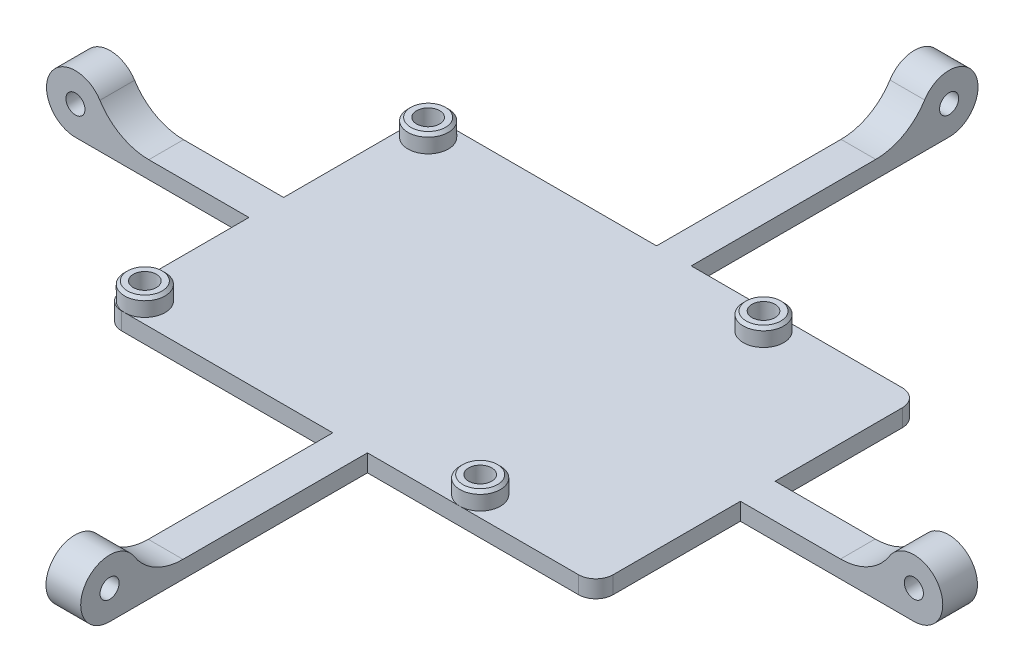
SolidWorks part; units mm, degrees
ref_plane "Front Plane" through (0, 0, 0) normal (0, 0, 1) x (1, 0, 0)
ref_plane "Top Plane" through (0, 0, 0) normal (0, 1, 0) x (1, 0, 0)
ref_plane "Right Plane" through (0, 0, 0) normal (1, 0, 0) x (0, 0, -1)
sketch "Sketch1" plane through (0, 0, 0) normal (0, 1, 0) x (1, 0, 0)
  line L0 (-39, 24.5) -> (-39, -24.5) construction
  line L1 (-39.5, -28) -> (39.5, -28)
  line L2 (-42.5, -25) -> (-42.5, 25)
  line L3 (-39.5, 28) -> (39.5, 28)
  line L4 (42.5, -25) -> (42.5, 25)
  line L5 (-42.5, -28) -> (42.5, 28) construction
  line L6 (-42.5, 28) -> (42.5, -28) construction
  line L7 (-39, 24.5) -> (19, 24.5) construction
  line L8 (-39, -24.5) -> (19, -24.5) construction
  circle A0 centre (-39, -24.5) radius 2
  circle A1 centre (-39, 24.5) radius 2
  circle A2 centre (19, 24.5) radius 2
  circle A3 centre (19, -24.5) radius 2
  arc A4 (39.5, 28) -> (42.5, 25) centre (39.5, 25) cw
  arc A5 (39.5, -28) -> (42.5, -25) centre (39.5, -25) ccw
  arc A6 (-39.5, -28) -> (-42.5, -25) centre (-39.5, -25) cw
  arc A7 (-42.5, 25) -> (-39.5, 28) centre (-39.5, 25) cw
  point P0 (0, 0)
  dimension "D3" = 4
  dimension "D8" = 3
  dimension "D1" = 56
  dimension "D2" = 85
  dimension "D4" = 3.5
  dimension "D5" = 3.5
  dimension "D6" = 3.5
  dimension "D7" = 58
extrude "Boss-Extrude1" add sketch "Sketch1" along normal blind 3
sketch "Sketch3" plane through (0, 3, 0) normal (0, 1, 0) x (1, 0, 0)
  line L0 (-72.5, 0) -> (72.5, 0) construction
  line L1 (42.5, -25) -> (42.5, 25) construction
  line L2 (0, 72.5) -> (0, -72.5) construction
  line L3 (-3, 3) -> (-72.5, 3)
  line L5 (-3, -3) -> (-72.5, -3)
  line L6 (-72.5, 3) -> (-72.5, -3)
  line L7 (-3, 3) -> (-3, 72.5)
  line L9 (42.5, 3) -> (42.5, -3)
  line L12 (3, 3) -> (3, 72.5)
  line L13 (3, 72.5) -> (-3, 72.5)
  line L14 (3, 3) -> (72.5, 3)
  line L15 (3, -3) -> (72.5, -3)
  line L16 (72.5, -3) -> (72.5, 3)
  line L17 (3, -3) -> (3, -72.5)
  line L18 (-3, -3) -> (-3, -72.5)
  line L19 (-3, -72.5) -> (3, -72.5)
  point P4 (0, 0)
  point P18 (0, 0)
  point P28 (0, 0)
  dimension "D1" = 30
  dimension "D2" = 6
  dimension "D3" = 4
extrude "Boss-Extrude3" add sketch "Sketch3" against normal blind 3 contours L5 L6 L3 L7 L13 L12 L14 L16 L15 L17 L19 L18
ref_axis "Axis1" through (0, 0, 0) along (0, 1, 0)
sketch "Sketch2" plane through (0, 3, 0) normal (0, 1, 0) x (1, 0, 0)
  circle A0 centre (19, 24.5) radius 2 construction
  circle A1 centre (19, -24.5) radius 2 construction
  circle A2 centre (-39, -24.5) radius 2 construction
  circle A3 centre (-39, 24.5) radius 2 construction
  circle A4 centre (19, 24.5) radius 2
  circle A5 centre (19, -24.5) radius 2
  circle A6 centre (-39, -24.5) radius 2
  circle A7 centre (-39, 24.5) radius 2
  circle A8 centre (-39, -24.5) radius 3.5
  circle A9 centre (-39, 24.5) radius 3.5
  circle A10 centre (19, 24.5) radius 3.5
  circle A11 centre (19, -24.5) radius 3.5
  dimension "D1" = 7
extrude "Boss-Extrude2" add sketch "Sketch2" along normal blind 3
sketch "Sketch4" plane through (0, 0, 3) normal (0, 0, 1) x (1, 0, 0)
  line L0 (-72.5, 0) -> (-42.5, 0) construction
  line L1 (-72.5, 0) -> (-72.5, 3) construction
  circle A0 centre (-72.5, 5) radius 1.65
  circle A1 centre (-72.5, 5) radius 5
  dimension "D1" = 3.3
  dimension "D2" = 10
extrude "Boss-Extrude4" add sketch "Sketch4" against normal up to surface (6 mm away) up to face at (-57.5, 1.5, -3)
fillet "Fillet1" radius 10 1 edges at (-67.9174, 3, 0)
sketch "Sketch6" plane through (3, 0, 0) normal (1, 0, 0) x (0, 0, -1)
  circle A0 centre (-72.5928, 4.9991) radius 5
  circle A1 centre (-72.5928, 4.9991) radius 1.65
  dimension "D1" = 3.3
  dimension "D2" = 10
extrude "Boss-Extrude5" add sketch "Sketch6" against normal up to surface (6 mm away) up to face at (-3, 1.5, 50.25)
fillet "Fillet2" radius 10 1 edges at (0, 3, 68.0099)
pattern_circular "CirPattern4" count 2 over 360 about axis through (0, 0, 0) along (0, 1, 0) of "Boss-Extrude3", "Boss-Extrude4", "Fillet1"
mirror "Mirror1" about plane through (0, 0, 0) normal (0, 0, 1) of "Fillet2", "Boss-Extrude5"
chamfer "Chamfer1" distance 0.5 angle 45 4 edges at (-39, 6, -21) (19, 6, -21) (19, 6, 28) (-39, 6, 28)
